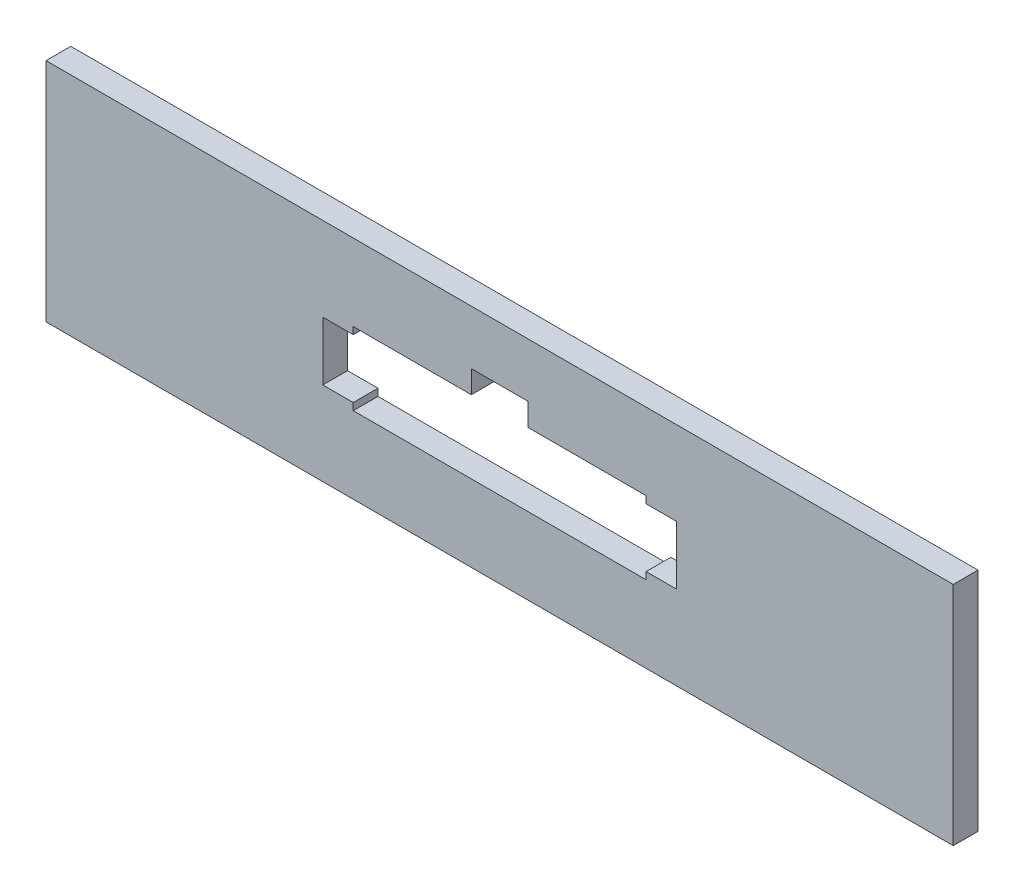
SolidWorks part; units mm, degrees
ref_plane "Front Plane" through (0, 0, 0) normal (0, 0, 1) x (1, 0, 0)
ref_plane "Top Plane" through (0, 0, 0) normal (0, 1, 0) x (1, 0, 0)
ref_plane "Right Plane" through (0, 0, 0) normal (1, 0, 0) x (0, 0, -1)
sketch "Sketch1" plane through (0, 0, 0) normal (0, 0, 1) x (1, 0, 0)
  line L0 (-19.1177, 0) -> (19.1177, 0) construction
  line L1 (0, -7.3085) -> (0, 7.3085) construction
  line L3 (-12.5, -2.075) -> (-10.35, -2.075)
  line L4 (-12.5, -2.075) -> (-12.5, 2.075)
  line L5 (-12.5, 2.075) -> (-10.35, 2.075)
  line L6 (12.5, -2.075) -> (12.5, 2.075)
  line L7 (10.35, 2.075) -> (10.35, 2.575)
  line L8 (-32.0669, -7.9977) -> (32.0669, -7.9977)
  line L9 (-10.35, -2.575) -> (10.35, -2.575)
  line L10 (-10.35, -2.575) -> (-10.35, -2.075)
  line L11 (-10.35, 2.575) -> (-2, 2.575)
  line L12 (10.35, -2.575) -> (10.35, -2.075)
  line L13 (-32.0669, -7.9977) -> (-32.0669, 7.9977)
  line L14 (-32.0669, 7.9977) -> (32.0669, 7.9977)
  line L15 (10.35, 2.075) -> (12.5, 2.075)
  line L16 (-2, 2.575) -> (-2, 4.175)
  line L17 (-2, 4.175) -> (2, 4.175)
  line L18 (2, 2.575) -> (2, 4.175)
  line L19 (-10.35, 2.075) -> (-10.35, 2.575)
  line L20 (32.0669, -7.9977) -> (32.0669, 7.9977)
  line L21 (2, 2.575) -> (10.35, 2.575)
  line L22 (10.35, -2.075) -> (12.5, -2.075)
  line L23 (-32.0669, -7.9977) -> (32.0669, 7.9977) construction
  line L24 (-32.0669, 7.9977) -> (32.0669, -7.9977) construction
  point P0 (0, 0)
  point P4 (0, 0)
  point P6 (0, 0)
  point P7 (0, 0)
  point P12 (0, 0)
  point P17 (0, 2.575)
  point P25 (0, 0)
  dimension "D1" = 4.15
  dimension "D2" = 25
  dimension "D3" = 20.7
  dimension "D4" = 5.15
  dimension "D5" = 4
  dimension "D6" = 1.6
extrude "Boss-Extrude1" add sketch "Sketch1" along normal blind 1.75
